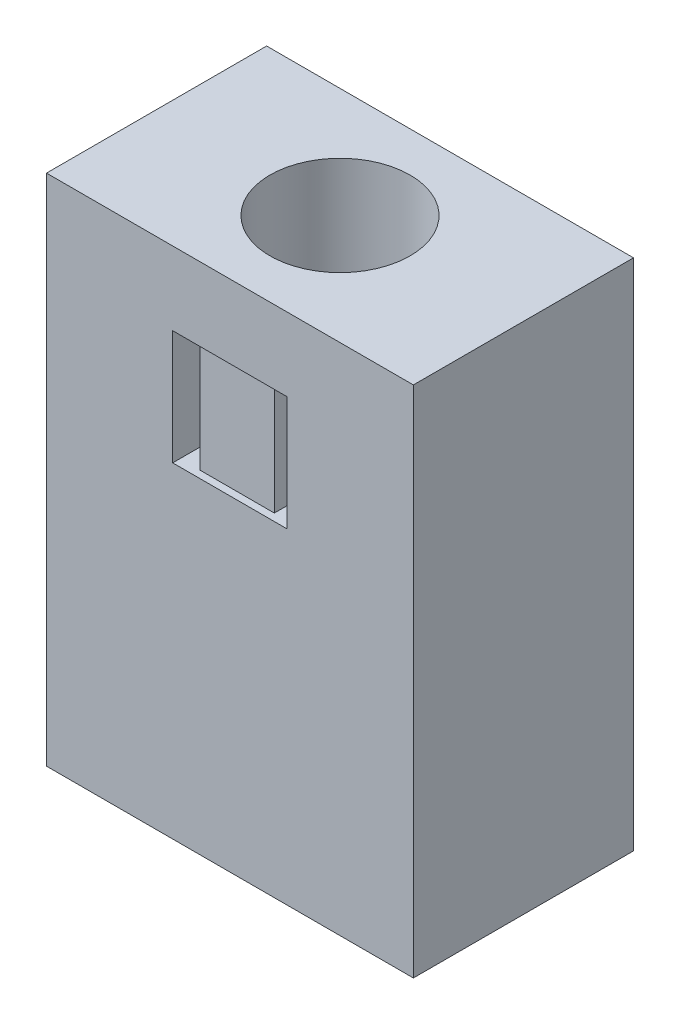
SolidWorks part; units mm, degrees
ref_plane "前视基准面" through (0, 0, 0) normal (0, 0, 1) x (1, 0, 0)
ref_plane "上视基准面" through (0, 0, 0) normal (0, 1, 0) x (1, 0, 0)
ref_plane "右视基准面" through (0, 0, 0) normal (1, 0, 0) x (0, 0, -1)
other "Configuration Table"
sketch "草图1" plane through (0, 0, 0) normal (0, 1, 0) x (1, 0, 0)
  line L0 (-25, 0) -> (25, 0) construction
  line L6 (-25, -15) -> (25, -15)
  line L7 (-25, -15) -> (-25, 15)
  line L8 (-25, 15) -> (25, 15)
  line L9 (25, -15) -> (25, 15)
  line L10 (-25, -15) -> (25, 15) construction
  line L11 (-25, 15) -> (25, -15) construction
  point P0 (0, 0)
  dimension "D1" = 50
  dimension "D2" = 30
extrude "凸台-拉伸1" add sketch "草图1" along normal blind 70
sketch "草图2" plane through (0, 0, 0) normal (0, -1, 0) x (1, 0, 0)
  circle A0 centre (0, 0) radius 9.55
  dimension "D1" = 19.1
extrude "切除-拉伸1" cut sketch "草图2" against normal blind 120
sketch "草图3" plane through (0, 0, 0) normal (0, 0, 1) x (1, 0, 0)
  line L0 (9.55, 70) -> (-9.55, 70) construction
  line L1 (-7.8, 44.4) -> (7.8, 44.4)
  line L2 (-7.8, 44.4) -> (-7.8, 60)
  line L3 (-7.8, 60) -> (7.8, 60)
  line L4 (7.8, 44.4) -> (7.8, 60)
  line L5 (-7.8, 44.4) -> (7.8, 60) construction
  line L6 (-7.8, 60) -> (7.8, 44.4) construction
  point P0 (0, 52.2)
  dimension "D1" = 15.6
  dimension "D2" = 15.6
  dimension "D3" = 10
extrude "切除-拉伸3" cut sketch "草图3" against normal blind 1 from offset 15
sketch "草图4" plane through (0, 0, 14) normal (0, 0, 1) x (1, 0, 0)
  line L0 (-5.05, 60) -> (-7.8, 60) construction
  line L2 (-5.05, 60) -> (-5.05, 44.4)
  line L4 (7.8, 44.4) -> (7.8, 60)
  line L5 (7.8, 60) -> (-7.8, 60)
  line L6 (-7.8, 60) -> (-7.8, 44.4)
  line L7 (-7.8, 44.4) -> (7.8, 44.4)
  line L8 (7.8, 44.4) -> (7.8, 60) construction
  line L9 (7.8, 60) -> (5.05, 60) construction
  line L10 (-7.8, 60) -> (-7.8, 44.4) construction
  line L11 (-7.8, 44.4) -> (-5.05, 44.4) construction
  line L12 (5.05, 60) -> (5.05, 44.4)
  line L13 (-7.8, 60) -> (-5.05, 60)
  line L14 (-7.8, 60) -> (-7.8, 44.4)
  line L15 (-7.8, 44.4) -> (-5.05, 44.4)
  line L16 (7.8, 60) -> (7.8, 44.4)
  line L17 (5.05, 60) -> (7.8, 60)
  line L18 (5.05, 44.4) -> (7.8, 44.4) construction
  line L19 (5.05, 44.4) -> (7.8, 44.4)
  dimension "D2" = 10.1
  dimension "D1" = 0
extrude "切除-拉伸4" cut sketch "草图4" against normal blind 3
